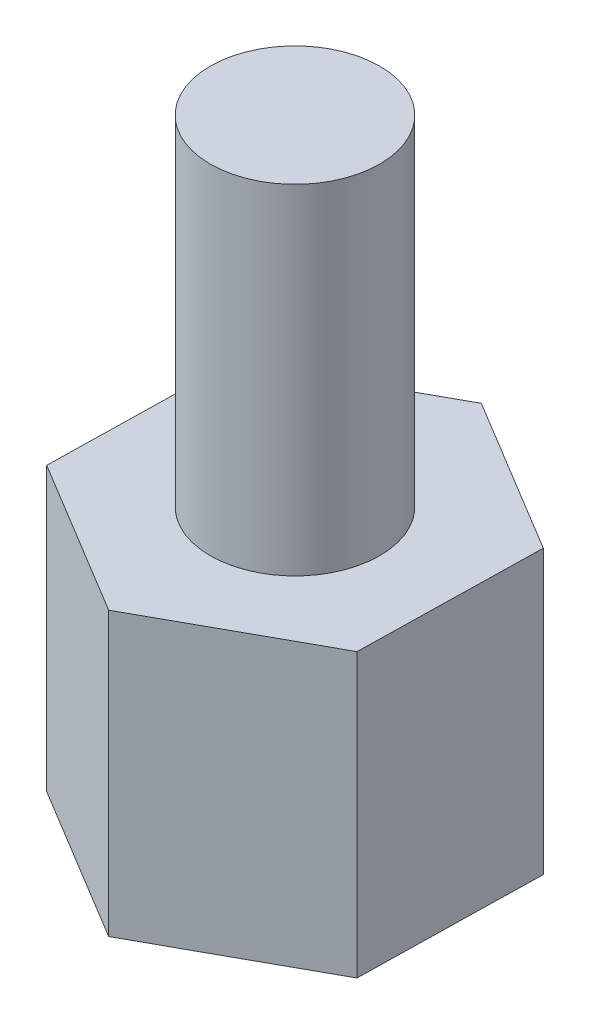
SolidWorks part; units mm, degrees
ref_plane "前视基准面" through (0, 0, 0) normal (0, 0, 1) x (1, 0, 0)
ref_plane "上视基准面" through (0, 0, 0) normal (0, 1, 0) x (1, 0, 0)
ref_plane "右视基准面" through (0, 0, 0) normal (1, 0, 0) x (0, 0, -1)
sketch "Sketch1" plane through (0, 0, 0) normal (0, 1, 0) x (1, 0, 0)
  line L1 (2.7678, -1.6711) -> (2.8311, 1.5614)
  line L2 (2.8311, 1.5614) -> (0.0633, 3.2325)
  line L3 (0.0633, 3.2325) -> (-2.7678, 1.6711)
  line L4 (-2.7678, 1.6711) -> (-2.8311, -1.5614)
  line L5 (-2.8311, -1.5614) -> (-0.0633, -3.2325)
  line L6 (-0.0633, -3.2325) -> (2.7678, -1.6711)
  circle A0 centre (0, 0) radius 2.8 construction
  circle A1 centre (0, 0) radius 1.5
  dimension "D1" = 5.6
extrude "Boss-Extrude1" add sketch "Sketch1" along normal blind 5
sketch "Sketch2" plane through (0, 5, 0) normal (0, 1, 0) x (1, 0, 0)
  circle A0 centre (0, 0) radius 1.5
extrude "Boss-Extrude2" add sketch "Sketch2" along normal blind 6 separate body
